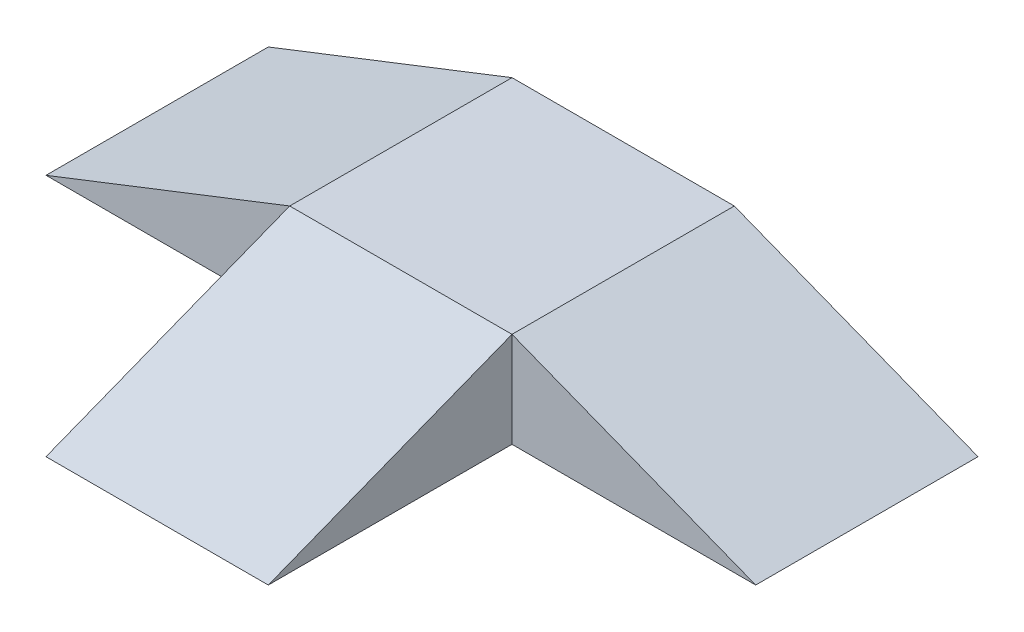
SolidWorks part; units mm, degrees
ref_plane "Front Plane" through (0, 0, 0) normal (0, 0, 1) x (1, 0, 0)
ref_plane "Top Plane" through (0, 0, 0) normal (0, 1, 0) x (1, 0, 0)
ref_plane "Right Plane" through (0, 0, 0) normal (1, 0, 0) x (0, 0, -1)
sketch "Sketch1" plane through (0, 0, 0) normal (0, 1, 0) x (1, 0, 0)
  line L1 (-175, -175) -> (175, -175)
  line L2 (-175, -175) -> (-175, 175)
  line L3 (-175, 175) -> (175, 175)
  line L4 (175, -175) -> (175, 175)
  line L5 (-175, -175) -> (175, 175) construction
  line L6 (-175, 175) -> (175, -175) construction
  point P0 (0, 0)
  dimension "D1" = 350
  dimension "D2" = 350
extrude "Boss-Extrude1" add sketch "Sketch1" along normal blind 150
sketch "Sketch2" plane through (0, 0, 0) normal (1, 0, 0) x (0, 0, -1)
  line L0 (-175, 150) -> (-175, 0)
  line L1 (-175, 0) -> (-558.7239, 0)
  line L2 (-558.7239, 0) -> (-175, 150)
  dimension "D1" = 412
extrude "Boss-Extrude2" add sketch "Sketch2" along normal mid plane 350
sketch "Sketch3" plane through (0, 0, 0) normal (0, 0, 1) x (1, 0, 0)
  line L0 (-175, 150) -> (-558.7239, 0)
  line L1 (-558.7239, 0) -> (-175, 0)
  line L2 (-175, 0) -> (-175, 150)
  line L3 (175, 150) -> (175, 0)
  line L4 (175, 0) -> (558.7239, 0)
  line L5 (558.7239, 0) -> (175, 150)
  dimension "D1" = 412
  dimension "D2" = 412
extrude "Boss-Extrude3" add sketch "Sketch3" along normal mid plane 350
